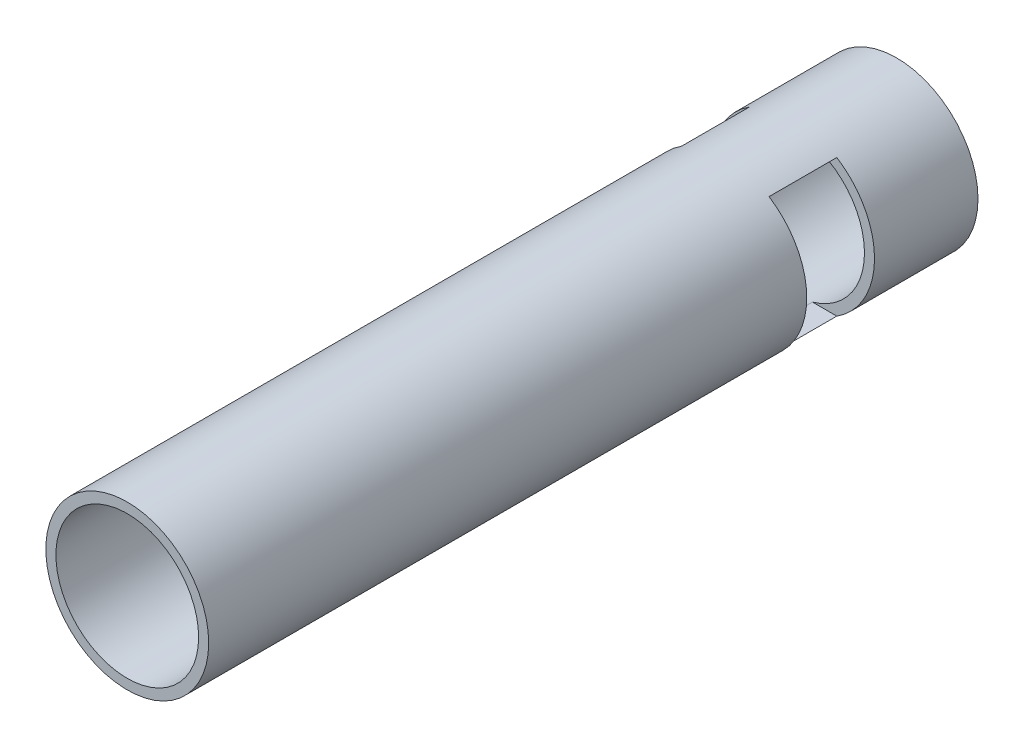
SolidWorks part; units mm, degrees
ref_plane "Front Plane" through (0, 0, 0) normal (0, 0, 1) x (1, 0, 0)
ref_plane "Top Plane" through (0, 0, 0) normal (0, 1, 0) x (1, 0, 0)
ref_plane "Right Plane" through (0, 0, 0) normal (1, 0, 0) x (0, 0, -1)
sketch "Sketch1" plane through (0, 0, 0) normal (0, 0, 1) x (1, 0, 0)
  circle A0 centre (0, 0) radius 38.9636
  circle A1 centre (0, 0) radius 44.45
  dimension "D1" = 88.9
  dimension "D2" = 5.4864
extrude "Boss-Extrude1" add sketch "Sketch1" along normal blind 420
sketch "Sketch2" plane through (0, 0, 0) normal (1, 0, 0) x (0, 0, -1)
  line L0 (0, 0) -> (-75, 0) construction
  line L1 (-75, 44.45) -> (-75, -44.45) construction
  line L2 (0, 44.45) -> (-420, 44.45) construction
  line L3 (-420, -44.45) -> (0, -44.45) construction
  point P9 (-75, 2)
  point P10 (-75, -2)
  point P11 (-75, -20.5)
  point P12 (-75, 20.5)
  dimension "D1" = 2
  dimension "D2" = 2
  dimension "D3" = 18.5
  dimension "D4" = 18.5
sketch "Sketch3" plane through (0, 0, 0) normal (1, 0, 0) x (0, 0, -1)
  line L1 (-93.5, 37.5) -> (-56.5, 37.5)
  line L2 (-93.5, 37.5) -> (-93.5, -37.5)
  line L3 (-93.5, -37.5) -> (-56.5, -37.5)
  line L4 (-56.5, 37.5) -> (-56.5, -37.5)
  line L5 (-93.5, 37.5) -> (-56.5, -37.5) construction
  line L6 (-93.5, -37.5) -> (-56.5, 37.5) construction
  point P0 (-75, 0)
  dimension "D1" = 75
  dimension "D2" = 37
extrude "Cut-Extrude1" cut sketch "Sketch3" against normal blind 50 and the other way blind 50
